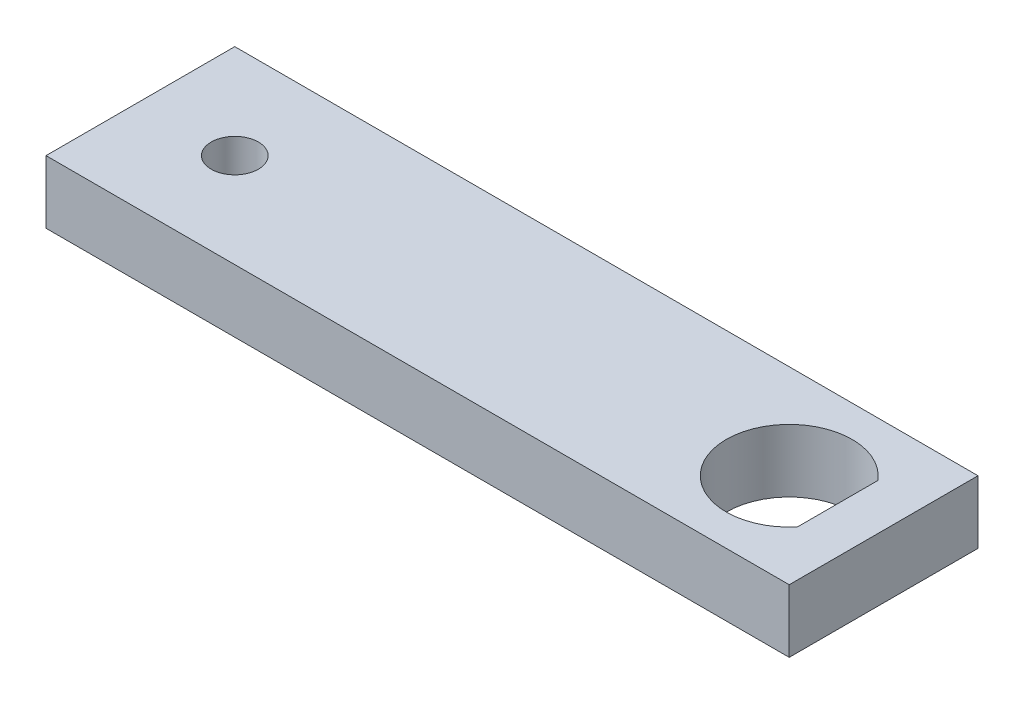
SolidWorks part; units mm, degrees
ref_plane "Front" through (0, 0, 0) normal (0, 0, 1) x (1, 0, 0)
ref_plane "Top" through (0, 0, 0) normal (0, 1, 0) x (-1, 0, 0)
ref_plane "Right" through (0, 0, 0) normal (1, 0, 0) x (0, 0, -1)
sketch "Sketch1" plane through (0, 0, 0) normal (0, 0, 1) x (1, 0, 0)
  line L0 (0, 0) -> (75, 0)
  line L1 (0, 0) -> (0, 6.35)
  line L2 (75, 6.35) -> (0, 6.35)
  line L3 (75, 6.35) -> (75, 0)
  dimension "D1" = 6.35
  dimension "D2" = 75
extrude "Base-Extrude" add sketch "Sketch1" along normal blind 19.05
sketch "Sketch2" plane through (0, 6.35, 0) normal (0, 1, 0) x (-1, 0, 0)
  line L0 (-75, 19.05) -> (-75, 0) construction
  line L1 (-75, 19.05) -> (0, 19.05) construction
  line L2 (-70.3645, 5.4734) -> (-70.3645, 13.5766)
  arc A0 (-70.3645, 5.4734) -> (-70.3645, 13.5766) centre (-65.475, 9.525) ccw
  dimension "D1" = 12.7
  dimension "D2" = 9.525
  dimension "D3" = 9.525
  dimension "D4" = 4.8895
extrude "Cut-Extrude1" cut sketch "Sketch2" against normal through all
sketch "Sketch3" plane through (0, 6.35, 0) normal (0, 1, 0) x (-1, 0, 0)
  line L0 (0, 19.05) -> (0, 0) construction
  circle A0 centre (-9.525, 9.525) radius 2.3813
  arc A1 (-70.3645, 5.4734) -> (-70.3645, 13.5766) centre (-65.475, 9.525) ccw construction
  point P5 (-65.475, 9.525)
  dimension "D1" = 4.7625
  dimension "D2" = 9.525
extrude "Cut-Extrude2" cut sketch "Sketch3" against normal through all
